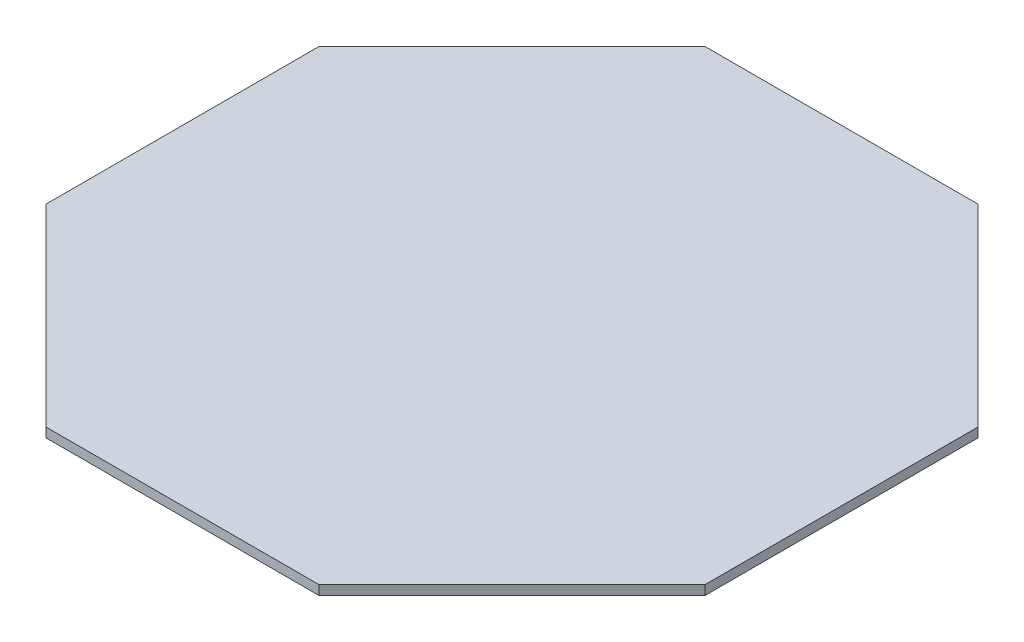
SolidWorks part; units mm, degrees
ref_plane "Front Plane" through (0, 0, 0) normal (0, 0, 1) x (1, 0, 0)
ref_plane "Top Plane" through (0, 0, 0) normal (0, 1, 0) x (1, 0, 0)
ref_plane "Right Plane" through (0, 0, 0) normal (1, 0, 0) x (0, 0, -1)
sketch "Sketch1" plane through (0, 0, 0) normal (0, 1, 0) x (1, 0, 0)
  line L5 (0, 0) -> (105.0183, 0)
  line L17 (105.0183, 0) -> (105.0183, 43.5)
  line L20 (0, 0) -> (105.0183, 43.5) construction
  line L21 (0, 0) -> (74.2591, 74.2591)
  line L22 (74.2591, 74.2591) -> (105.0183, 43.5)
  dimension "D1" = 43.5
  dimension "D2" = 22.5
extrude "Boss-Extrude1" add sketch "Sketch1" along normal blind 3
pattern_circular "CirPattern1" count 8 every 45 about axis through (0, 0, 0) along (0, 1, 0) of "Boss-Extrude1"
